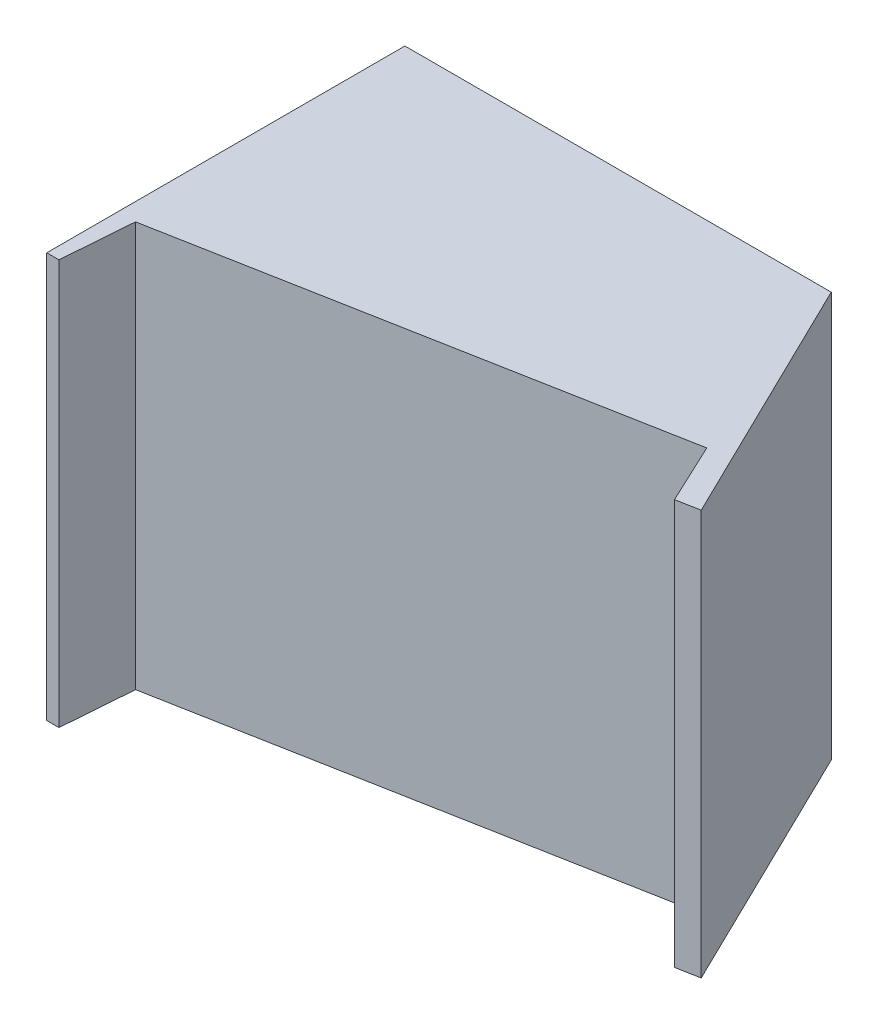
SolidWorks part; units mm, degrees
ref_plane "Front Plane" through (0, 0, 0) normal (0, 0, 1) x (1, 0, 0)
ref_plane "Top Plane" through (0, 0, 0) normal (0, 1, 0) x (1, 0, 0)
ref_plane "Right Plane" through (0, 0, 0) normal (1, 0, 0) x (0, 0, -1)
other "Graphic1"
other "Graphic (Closed) -1"
sketch "Sketch1" plane through (0, 0, 0) normal (0, 0, 1) x (1, 0, 0)
  line L1 (0, 0) -> (449.9783, 0)
  line L2 (0, 0) -> (0, 427.5737)
  line L3 (0, 427.5737) -> (449.9783, 427.5737)
  line L4 (449.9783, 0) -> (449.9783, 427.5737)
  point P4 (563.9613, 478.4222)
  point P5 (0, 0)
  dimension "D1" = 427.5737
  dimension "D2" = 449.9783
extrude "Boss-Extrude1" add sketch "Sketch1" along normal blind 378
draft "Draft2" type of draft neutral plane draft angle 26 faces to draft 1 face at (449.9783, 213.7869, 189) neutral plane through (0, 0, 0) neutral plane normal (0, 0, -1) parameters "D1"=26
sketch "Sketch2" plane through (0, 427.5737, 0) normal (0, 1, 0) x (1, 0, 0)
  line L0 (12.8564, -378) -> (18.6039, -302.8778)
  line L1 (18.6039, -302.8778) -> (526.6673, -208.0604)
  line L2 (526.6673, -208.0604) -> (556.8544, -272.3551)
  line L3 (556.8544, -272.3551) -> (580.6489, -267.9144)
  line L4 (634.3413, -378) -> (0, -378) construction
  line L5 (634.3413, -378) -> (449.9783, 0) construction
  line L6 (0, -378) -> (0, 0) construction
  line L7 (449.9783, 0) -> (0, 0) construction
  point P3 (12.8564, -378)
  point P8 (580.6489, -267.9144)
  dimension "D1" = 12.8564
  dimension "D2" = 18.6039
  dimension "D3" = 526.6673
  dimension "D4" = 556.8544
  dimension "D5" = 580.6489
  dimension "D6" = 208.0604
  dimension "D7" = 272.3551
extrude "Cut-Extrude1" cut sketch "Sketch2" against normal through all and the other way through all flip side to cut
